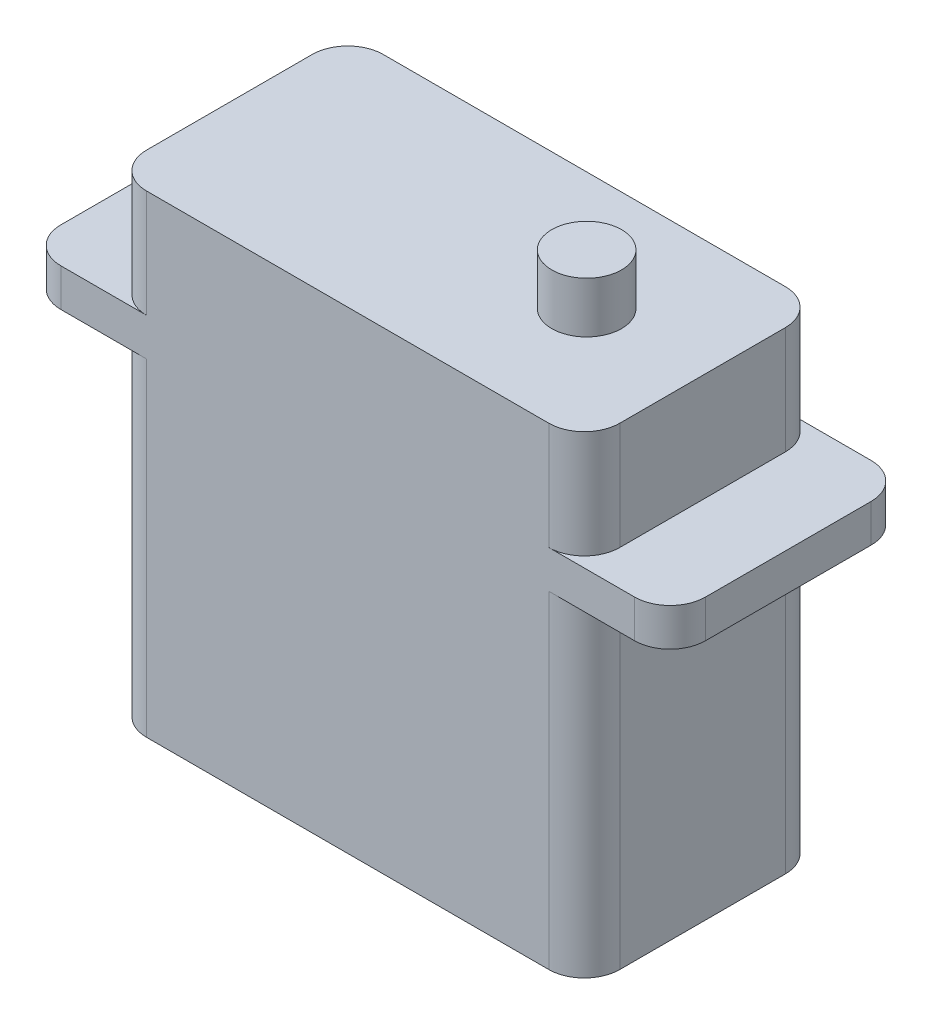
SolidWorks part; units mm, degrees
ref_plane "Front Plane" through (0, 0, 0) normal (0, 0, 1) x (1, 0, 0)
ref_plane "Top Plane" through (0, 0, 0) normal (0, 1, 0) x (1, 0, 0)
ref_plane "Right Plane" through (0, 0, 0) normal (1, 0, 0) x (0, 0, -1)
sketch "Sketch1" plane through (0, 0, 0) normal (0, 1, 0) x (1, 0, 0)
  line L1 (-20, -10) -> (20, -10)
  line L2 (-20, -10) -> (-20, 10)
  line L3 (-20, 10) -> (20, 10)
  line L4 (20, -10) -> (20, 10)
  line L5 (-20, -10) -> (20, 10) construction
  line L6 (-20, 10) -> (20, -10) construction
  point P0 (0, 0)
  dimension "D1" = 40
  dimension "D2" = 20
extrude "Boss-Extrude1" add sketch "Sketch1" along normal blind 40
sketch "Sketch2" plane through (0, 0, 10) normal (0, 0, 1) x (1, 0, 0)
  line L0 (-20, 0) -> (20, 0) construction
  line L1 (-27.25, 27.7) -> (27.25, 27.7)
  line L2 (-27.25, 27.7) -> (-27.25, 30.9)
  line L3 (-27.25, 30.9) -> (27.25, 30.9)
  line L4 (27.25, 27.7) -> (27.25, 30.9)
  point P6 (0, 27.7)
  dimension "D1" = 27.7
  dimension "D2" = 54.5
  dimension "D3" = 3.2
extrude "Boss-Extrude2" add sketch "Sketch2" against normal up to surface (20 mm away) contours L3 L4 L1 L2 up to face at (0, 20, -10)
fillet "Fillet1" radius 3 12 edges at (20, 13.85, -10) (20, 13.85, 10) (27.25, 29.3, 10) (27.25, 29.3, -10) (20, 35.45, -10) (20, 35.45, 10) (-27.25, 29.3, 10) (-27.25, 29.3, -10) (-20, 35.45, -10) (-20, 13.85, -10) (-20, 13.85, 10) (-20, 35.45, 10)
sketch "Sketch3" plane through (0, 40, 0) normal (0, 1, 0) x (1, 0, 0)
  line L0 (20, -7) -> (20, 7) construction
  circle A0 centre (10.2, 0) radius 2.95
  dimension "D2" = 5.9
  dimension "D1" = 9.8
extrude "Boss-Extrude3" add sketch "Sketch3" along normal blind 4.3
sketch "Sketch4" plane through (0, 0, 10) normal (0, 0, 1) x (1, 0, 0)
  line L0 (-17, 27.7) -> (17, 27.7) construction
  text T0 "<b>BETU 25kg</b>\r\n" font "Century Gothic" height 3.175
scale "Scale1" bodies to scale 103 scale about centroid uniform scaling yes scale factor 1.025
